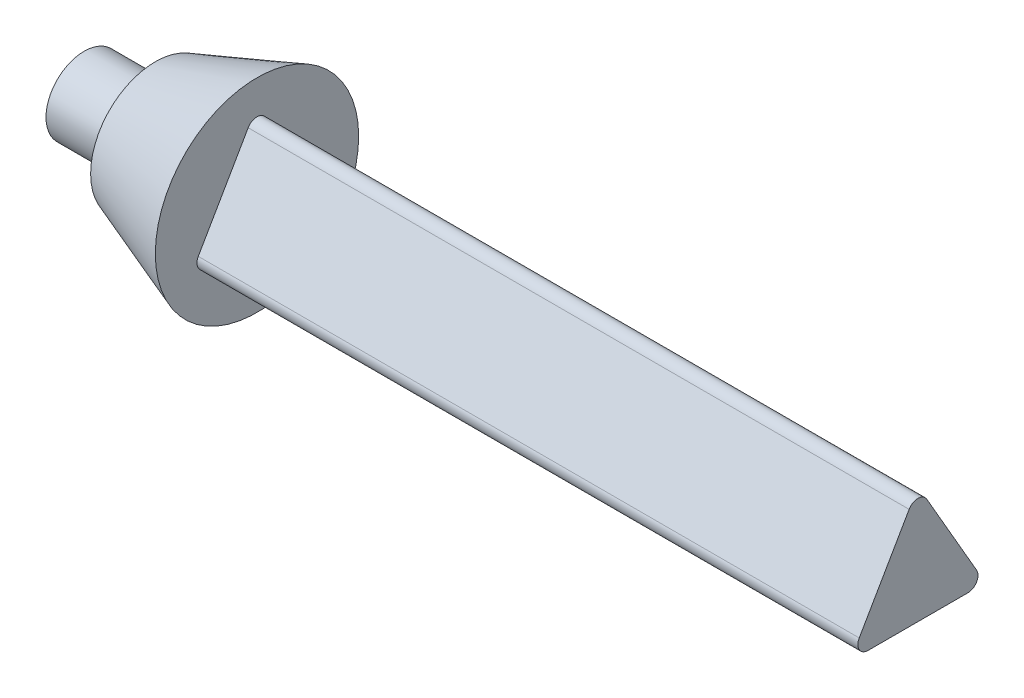
SolidWorks part; units mm, degrees
material "PET"
ref_plane "Front Plane" through (0, 0, 0) normal (0, 0, 1) x (1, 0, 0)
ref_plane "Top Plane" through (0, 0, 0) normal (0, 1, 0) x (1, 0, 0)
ref_plane "Right Plane" through (0, 0, 0) normal (1, 0, 0) x (0, 0, -1)
sketch "Sketch1" plane through (0, 0, 0) normal (0, 0, 1) x (1, 0, 0)
  line L0 (0, 0) -> (0, 2)
  line L1 (0, 2) -> (-2, 1.2721)
  line L2 (-2, 1.2721) -> (-2, 0)
  line L3 (-2, 0) -> (0, 0)
  dimension "D1" = 2
  dimension "D2" = 2
  dimension "D3" = 20
revolve "Revolve1" add sketch "Sketch1" angle 360 about L3
sketch "Sketch2" plane through (0, 0, 0) normal (1, 0, 0) x (0, 0, -1)
  line L0 (0, 1.5333) -> (-1.3279, -0.7667)
  line L1 (-1.3279, -0.7667) -> (1.3279, -0.7667)
  line L2 (1.3279, -0.7667) -> (0, 1.5333)
  circle A0 centre (0, 0) radius 1.5333 construction
  dimension "D1" = 2.3
extrude "Boss-Extrude1" add sketch "Sketch2" along normal blind 13
sketch "Sketch3" plane through (-2, 0, 0) normal (-1, 0, 0) x (0, 0, 1)
  circle A0 centre (0, 0) radius 0.75
  dimension "D1" = 1.5
extrude "Boss-Extrude2" add sketch "Sketch3" along normal blind 1.4
fillet "Fillet1" radius 0.2 3 edges at (6.5, -0.7667, -1.3279) (6.5, 1.5333, 0) (6.5, -0.7667, 1.3279)
